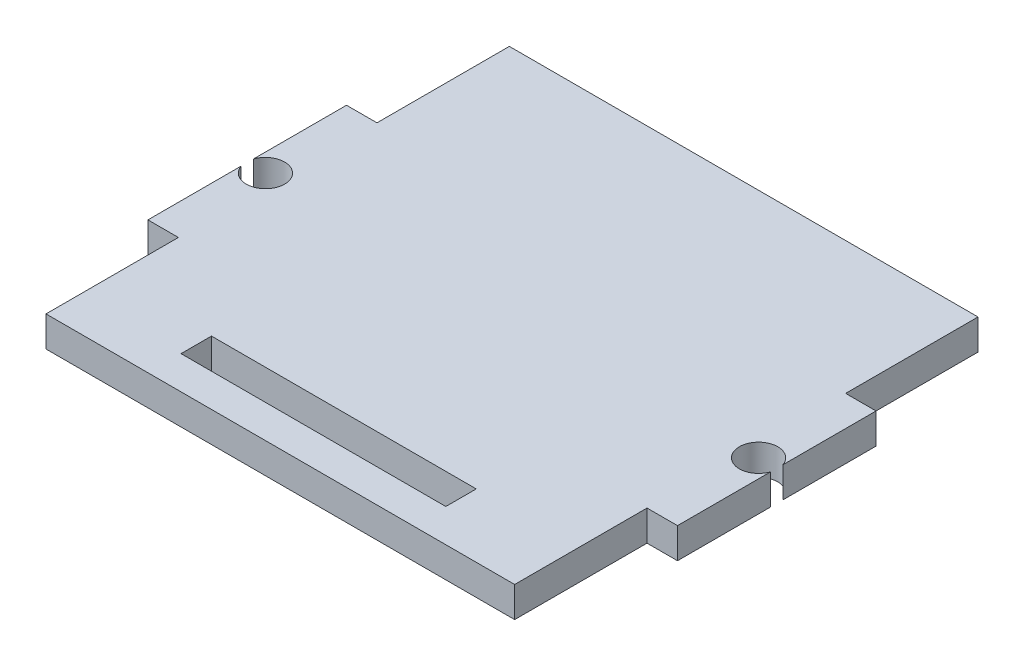
SolidWorks part; units mm, degrees
ref_plane "Front Plane" through (0, 0, 0) normal (0, 0, 1) x (1, 0, 0)
ref_plane "Top Plane" through (0, 0, 0) normal (0, 1, 0) x (1, 0, 0)
ref_plane "Right Plane" through (0, 0, 0) normal (1, 0, 0) x (0, 0, -1)
sketch "Sketch1" plane through (0, 0, 0) normal (0, 1, 0) x (1, 0, 0)
  line L0 (3.5878, 22.225) -> (47.2123, 22.225) construction
  line L1 (2.921, 0) -> (47.879, 0)
  line L2 (0, 12.7) -> (0, 21.6404)
  line L3 (2.921, 44.45) -> (47.879, 44.45)
  line L4 (50.8, 12.7) -> (50.8, 21.6404)
  line L5 (0, 22.8096) -> (0, 31.75)
  line L6 (50.8, 22.8096) -> (50.8, 31.75)
  line L7 (0, 31.75) -> (2.921, 31.75)
  line L8 (2.921, 44.45) -> (2.921, 31.75)
  line L9 (25.4, 44.45) -> (25.4, 0) construction
  line L10 (50.8, 31.75) -> (47.879, 31.75)
  line L11 (47.879, 44.45) -> (47.879, 31.75)
  line L12 (50.8, 12.7) -> (47.879, 12.7)
  line L13 (47.879, 0) -> (47.879, 12.7)
  line L14 (0, 12.7) -> (2.921, 12.7)
  line L15 (2.921, 0) -> (2.921, 12.7)
  line L16 (12.7, 4.6355) -> (2.921, 4.6355) construction
  line L17 (12.7, 6.096) -> (38.1, 6.096)
  line L18 (12.7, 6.096) -> (12.7, 3.175)
  line L19 (12.7, 3.175) -> (38.1, 3.175)
  line L20 (38.1, 6.096) -> (38.1, 3.175)
  line L21 (38.1, 4.6355) -> (47.879, 4.6355) construction
  arc A0 (0, 21.6404) -> (0, 22.8096) centre (1.7463, 22.225) ccw
  arc A1 (50.8, 21.6404) -> (50.8, 22.8096) centre (49.0538, 22.225) cw
  dimension "D7" = 3.683
  dimension "D1" = 19.05
  dimension "D2" = 44.958
  dimension "D3" = 2.921
  dimension "D4" = 12.7
  dimension "D5" = 2.921
  dimension "D6" = 12.7
  dimension "D8" = 1.7463
  dimension "D9" = 25.4
  dimension "D10" = 2.921
  dimension "D11" = 3.175
extrude "Boss-Extrude1" add sketch "Sketch1" along normal blind 2.921
